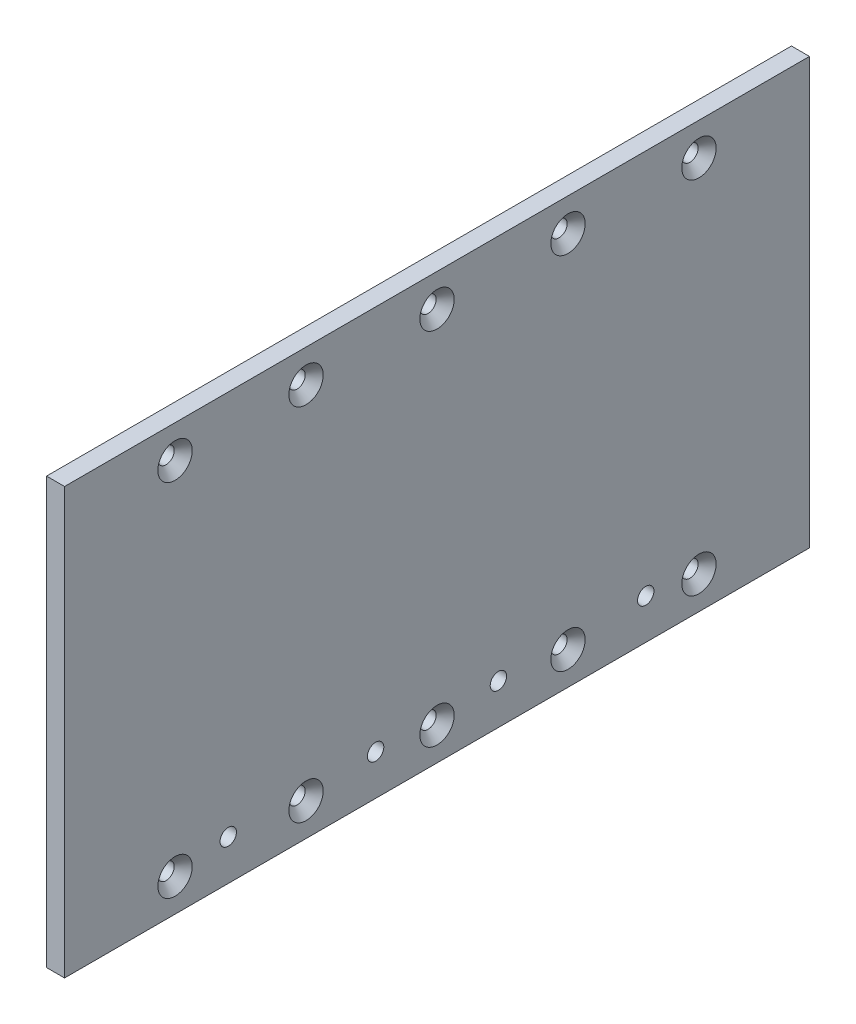
SolidWorks part; units mm, degrees
material "Aluminum"
ref_plane "Front Plane" through (0, 0, 0) normal (0, 0, 1) x (1, 0, 0)
ref_plane "Top Plane" through (0, 0, 0) normal (0, 1, 0) x (1, 0, 0)
ref_plane "Right Plane" through (0, 0, 0) normal (1, 0, 0) x (0, 0, -1)
sketch "Sketch1" plane through (0, 0, 0) normal (1, 0, 0) x (0, 0, -1)
  line L1 (113.75, -65) -> (-113.75, -65)
  line L2 (113.75, -65) -> (113.75, 65)
  line L3 (113.75, 65) -> (-113.75, 65)
  line L4 (-113.75, -65) -> (-113.75, 65)
  line L5 (113.75, -65) -> (-113.75, 65) construction
  line L6 (113.75, 65) -> (-113.75, -65) construction
  point P0 (0, 0)
  dimension "D1" = 227.5
  dimension "D2" = 130
extrude "Boss-Extrude1" add sketch "Sketch1" along normal blind 5.5
hole_wizard "CSK for M5 Hex Socket Countersunk Cap Screw1" positions "Sketch6" profile "Sketch5" countersink size "M5" standard "ISO" end condition through all
sketch "Sketch6" plane through (5.5, 0, 0) normal (1, 0, 0) x (0, 0, -1)
  point P0 (80, 55)
  point P3 (40, 55)
  point P6 (0, 55)
  point P8 (-40, 55)
  point P11 (-80, 55)
  point P14 (-80, -55)
  point P17 (-40, -55)
  point P20 (0, -55)
  point P23 (40, -55)
  point P26 (80, -55)
sketch "Sketch5" plane through (5.5, 55, -80) normal (0, 1, 0) x (0, 0, -1)
  line L0 (0, 0) -> (0, 5.5)
  line L1 (0, 5.5) -> (2.5, 5.5)
  line L2 (2.5, 5.5) -> (2.5, 2.75)
  line L3 (2.5, 2.75) -> (5.25, 0)
  line L5 (5.25, 0) -> (0, 0)
  line L6 (-2.5, 2.75) -> (-5.25, 0) construction
  line L11 (0, -6.35) -> (0, 107.95) construction
  dimension "Thru Hole Dia." = 5
  dimension "Thru Hole Depth" = 5.5
  dimension "Near C'Sink Dia." = 10.5
  dimension "Near C'Sink Angle" = 90
hole_wizard "Tap Drill for M5x0.8 Tap1" positions "Sketch8" profile "Sketch7" hole size "M5x0.8" standard "ANSI Metric" end condition through all
sketch "Sketch8" plane through (5.5, 0, 0) normal (1, 0, 0) x (0, 0, -1)
  point P0 (-63.75, -52.6538)
  point P3 (-18.75, -52.6538)
  point P6 (18.75, -52.6538)
  point P9 (63.75, -52.6538)
sketch "Sketch7" plane through (5.5, -52.6538, 63.75) normal (0, 1, 0) x (0, 0, -1)
  line L0 (0, 0) -> (0, 5.5)
  line L1 (0, 5.5) -> (2.5, 5.5)
  line L2 (2.5, 5.5) -> (2.5, 0)
  line L5 (2.5, 0) -> (0, 0)
  line L11 (0, -6.35) -> (0, 107.95) construction
  dimension "Thru Hole Dia." = 5
  dimension "Thru Hole Depth" = 5.5
